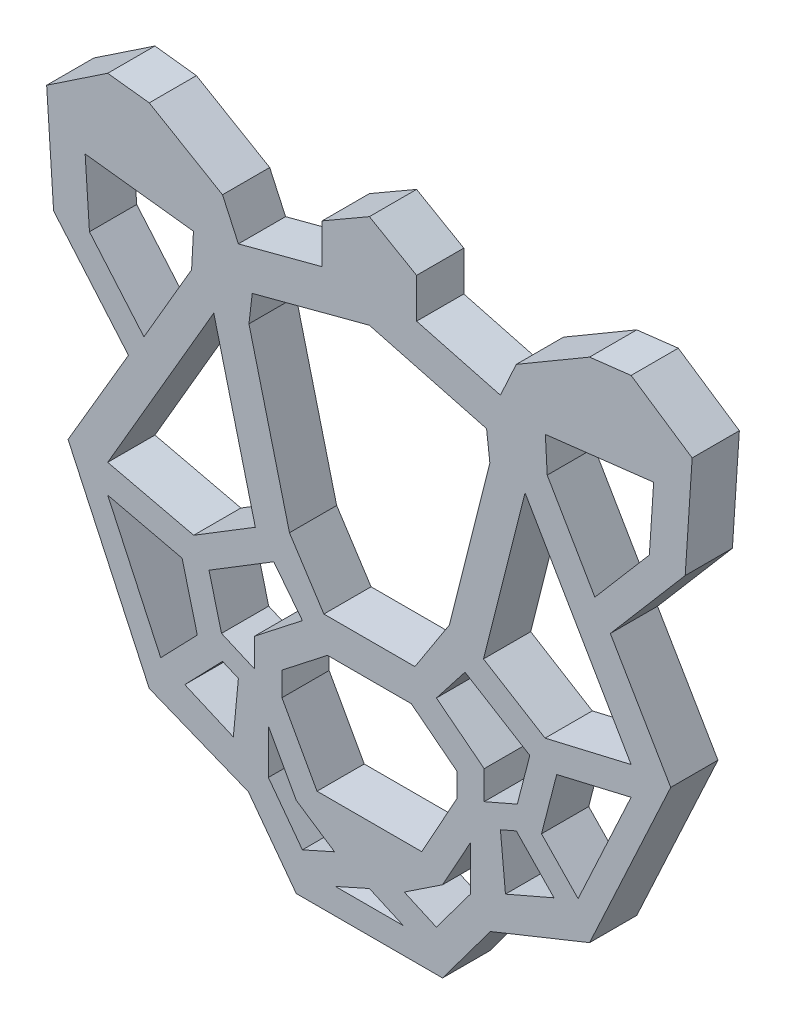
SolidWorks part; units mm, degrees
ref_plane "Front Plane" through (0, 0, 0) normal (0, 0, 1) x (1, 0, 0)
ref_plane "Top Plane" through (0, 0, 0) normal (0, 1, 0) x (1, 0, 0)
ref_plane "Right Plane" through (0, 0, 0) normal (1, 0, 0) x (0, 0, -1)
sketch "Sketch1" plane through (0, 0, 0) normal (0, 0, 1) x (1, 0, 0)
  line L0 (65.9458, 130.7183) -> (292.0603, 114.9068) construction
  line L1 (127.703, 180.9659) -> (127.703, 53.5207) construction
  line L2 (127.703, 180.9659) -> (99.9429, 173.6319)
  line L3 (99.9429, 173.6319) -> (96.5789, 180.9659)
  line L4 (96.5789, 180.9659) -> (81.0528, 190.0638)
  line L5 (81.0528, 190.0638) -> (72.2546, 191.0989)
  line L6 (72.2546, 191.0989) -> (59.3162, 182.4301)
  line L7 (59.3162, 182.4301) -> (60.7903, 160.1116)
  line L8 (60.7903, 160.1116) -> (76.6537, 141.5446)
  line L9 (76.6537, 141.5446) -> (63.8551, 119.7029)
  line L10 (63.8551, 119.7029) -> (81.0528, 82.6114)
  line L11 (81.0528, 82.6114) -> (102.0708, 74.1541)
  line L12 (102.0708, 74.1541) -> (112.2055, 60.5522)
  line L13 (112.2055, 60.5522) -> (143.2006, 60.5522)
  line L14 (67.4743, 173.8972) -> (68.3872, 160.0766)
  line L15 (68.3872, 160.0766) -> (79.931, 146.5652)
  line L16 (79.931, 146.5652) -> (90.0266, 163.9177)
  line L17 (90.0266, 163.9177) -> (90.4234, 171.1974)
  line L18 (90.4234, 171.1974) -> (67.4743, 173.8972)
  line L19 (127.703, 172.5775) -> (102.8796, 166.0193)
  line L20 (102.8796, 166.0193) -> (102.1805, 160.0766)
  line L21 (102.1805, 160.0766) -> (110.7657, 126.0385)
  line L22 (110.7657, 126.0385) -> (118.0587, 114.7661)
  line L23 (118.0587, 114.7661) -> (137.3473, 114.7661)
  line L24 (136.5861, 107.5722) -> (118.8199, 107.5722)
  line L25 (118.8199, 107.5722) -> (109.1724, 100.0375)
  line L26 (109.1724, 100.0375) -> (109.1724, 94.9661)
  line L27 (109.1724, 94.9661) -> (116.6085, 81.5301)
  line L28 (116.6085, 81.5301) -> (138.7976, 81.5301)
  line L29 (127.703, 69.2226) -> (120.5012, 66.0034)
  line L30 (120.5012, 66.0034) -> (134.9049, 66.0034)
  line L31 (106.2983, 88.3331) -> (112.2055, 77.6595)
  line L32 (112.2055, 77.6595) -> (120.3143, 72.2653)
  line L33 (120.3143, 72.2653) -> (113.5073, 69.2226)
  line L34 (113.5073, 69.2226) -> (106.2983, 78.898)
  line L35 (106.2983, 78.898) -> (106.2983, 88.3331)
  line L36 (88.5849, 87.0771) -> (98.8717, 82.6114)
  line L37 (98.8717, 82.6114) -> (99.9429, 93.8932)
  line L38 (99.9429, 93.8932) -> (96.5789, 95.3536)
  line L39 (96.5789, 95.3536) -> (88.5849, 87.0771)
  line L40 (88.0136, 109.9932) -> (91.2375, 97.4942)
  line L41 (91.2375, 97.4942) -> (83.484, 89.4668)
  line L42 (83.484, 89.4668) -> (72.2546, 113.686)
  line L43 (72.2546, 113.686) -> (88.0136, 109.9932)
  line L44 (93.7147, 110.6414) -> (96.3638, 100.3712)
  line L45 (72.2546, 119.7029) -> (94.7296, 158.3334)
  line L46 (96.3638, 100.3712) -> (103.3816, 97.3246)
  line L47 (103.3816, 97.3246) -> (103.3816, 103.3759)
  line L48 (103.3816, 103.3759) -> (113.5073, 111.2839)
  line L49 (113.5073, 111.2839) -> (107.4424, 119.0495)
  line L50 (107.4424, 119.0495) -> (93.7147, 110.6414)
  line L51 (94.7296, 158.3334) -> (103.533, 123.4302)
  line L52 (103.533, 123.4302) -> (90.4763, 115.433)
  line L53 (90.4763, 115.433) -> (72.2546, 119.7029)
  line L54 (164.9298, 115.433) -> (183.1514, 119.7029)
  line L55 (151.873, 123.4302) -> (164.9298, 115.433)
  line L56 (160.6765, 158.3334) -> (151.873, 123.4302)
  line L57 (147.9636, 119.0495) -> (161.6913, 110.6414)
  line L58 (141.8988, 111.2839) -> (147.9636, 119.0495)
  line L59 (152.0245, 103.3759) -> (141.8988, 111.2839)
  line L60 (152.0245, 97.3246) -> (152.0245, 103.3759)
  line L61 (159.0423, 100.3712) -> (152.0245, 97.3246)
  line L62 (183.1514, 119.7029) -> (160.6765, 158.3334)
  line L63 (161.6913, 110.6414) -> (159.0423, 100.3712)
  line L64 (183.1514, 113.686) -> (167.3925, 109.9932)
  line L65 (171.9221, 89.4668) -> (183.1514, 113.686)
  line L66 (164.1685, 97.4942) -> (171.9221, 89.4668)
  line L67 (167.3925, 109.9932) -> (164.1685, 97.4942)
  line L68 (158.8272, 95.3536) -> (166.8212, 87.0771)
  line L69 (155.4632, 93.8932) -> (158.8272, 95.3536)
  line L70 (156.5344, 82.6114) -> (155.4632, 93.8932)
  line L71 (166.8212, 87.0771) -> (156.5344, 82.6114)
  line L72 (149.1078, 78.898) -> (149.1078, 88.3331)
  line L73 (141.8988, 69.2226) -> (149.1078, 78.898)
  line L74 (135.0918, 72.2653) -> (141.8988, 69.2226)
  line L75 (143.2006, 77.6595) -> (135.0918, 72.2653)
  line L76 (149.1078, 88.3331) -> (143.2006, 77.6595)
  line L77 (127.703, 69.2226) -> (134.9049, 66.0034)
  line L78 (146.2337, 94.9661) -> (138.7976, 81.5301)
  line L79 (146.2337, 100.0375) -> (146.2337, 94.9661)
  line L80 (136.5861, 107.5722) -> (146.2337, 100.0375)
  line L81 (144.6404, 126.0385) -> (137.3473, 114.7661)
  line L82 (153.2256, 160.0766) -> (144.6404, 126.0385)
  line L83 (152.5265, 166.0193) -> (153.2256, 160.0766)
  line L84 (127.703, 172.5775) -> (152.5265, 166.0193)
  line L85 (164.9827, 171.1974) -> (187.9318, 173.8972)
  line L86 (165.3795, 163.9177) -> (164.9827, 171.1974)
  line L87 (175.475, 146.5652) -> (165.3795, 163.9177)
  line L88 (187.0189, 160.0766) -> (175.475, 146.5652)
  line L89 (187.9318, 173.8972) -> (187.0189, 160.0766)
  line L90 (153.3353, 74.1541) -> (143.2006, 60.5522)
  line L91 (174.3533, 82.6114) -> (153.3353, 74.1541)
  line L92 (191.551, 119.7029) -> (174.3533, 82.6114)
  line L93 (178.7524, 141.5446) -> (191.551, 119.7029)
  line L94 (194.6158, 160.1116) -> (178.7524, 141.5446)
  line L95 (196.0899, 182.4301) -> (194.6158, 160.1116)
  line L96 (183.1514, 191.0989) -> (196.0899, 182.4301)
  line L97 (174.3533, 190.0638) -> (183.1514, 191.0989)
  line L98 (158.8272, 180.9659) -> (174.3533, 190.0638)
  line L99 (155.4632, 173.6319) -> (158.8272, 180.9659)
  line L100 (127.703, 180.9659) -> (155.4632, 173.6319)
  point P52 (97.884, 101.8107)
  point P57 (107.4424, 119.0495)
  point P59 (113.5073, 111.2839)
  point P60 (120.3143, 66.0034)
  point P61 (0, 0)
  point P62 (0, 0)
  point P63 (118.8199, 107.5722)
  point P64 (0, 0)
  point P65 (0, 0)
  point P66 (70.2544, 130.6237)
  point P93 (127.703, 66.0034)
  point P94 (127.703, 81.5301)
  point P97 (127.703, 107.5722)
  point P98 (127.703, 114.7661)
  point P107 (127.703, 60.5522)
  point P117 (127.703, 173.6319)
  point P118 (103.0077, 160.0766)
  point P119 (127.703, 173.6319)
  point P120 (127.703, 172.5775)
  dimension "D1" = 7.2208
extrude "Boss-Extrude1" add sketch "Sketch1" along normal blind 10
sketch "Sketch2" plane through (0, 0, 10) normal (0, 0, 1) x (1, 0, 0)
  line L0 (127.703, 172.5775) -> (102.8796, 166.0193) construction
  line L1 (137.703, 186.7394) -> (127.703, 192.5129)
  line L2 (127.703, 192.5129) -> (117.703, 186.7394)
  line L3 (117.703, 186.7394) -> (117.703, 175.1924)
  line L4 (117.703, 175.1924) -> (123.9497, 171.5859)
  line L5 (131.4563, 171.5859) -> (137.703, 175.1924)
  line L6 (137.703, 175.1924) -> (137.703, 186.7394)
  line L7 (152.5265, 166.0193) -> (127.703, 172.5775) construction
  line L8 (127.703, 172.5775) -> (123.9497, 171.5859)
  line L9 (131.4563, 171.5859) -> (127.703, 172.5775)
  circle A0 centre (127.703, 180.9659) radius 10 construction
  dimension "D1" = 20
extrude "Boss-Extrude2" add sketch "Sketch2" against normal blind 10
